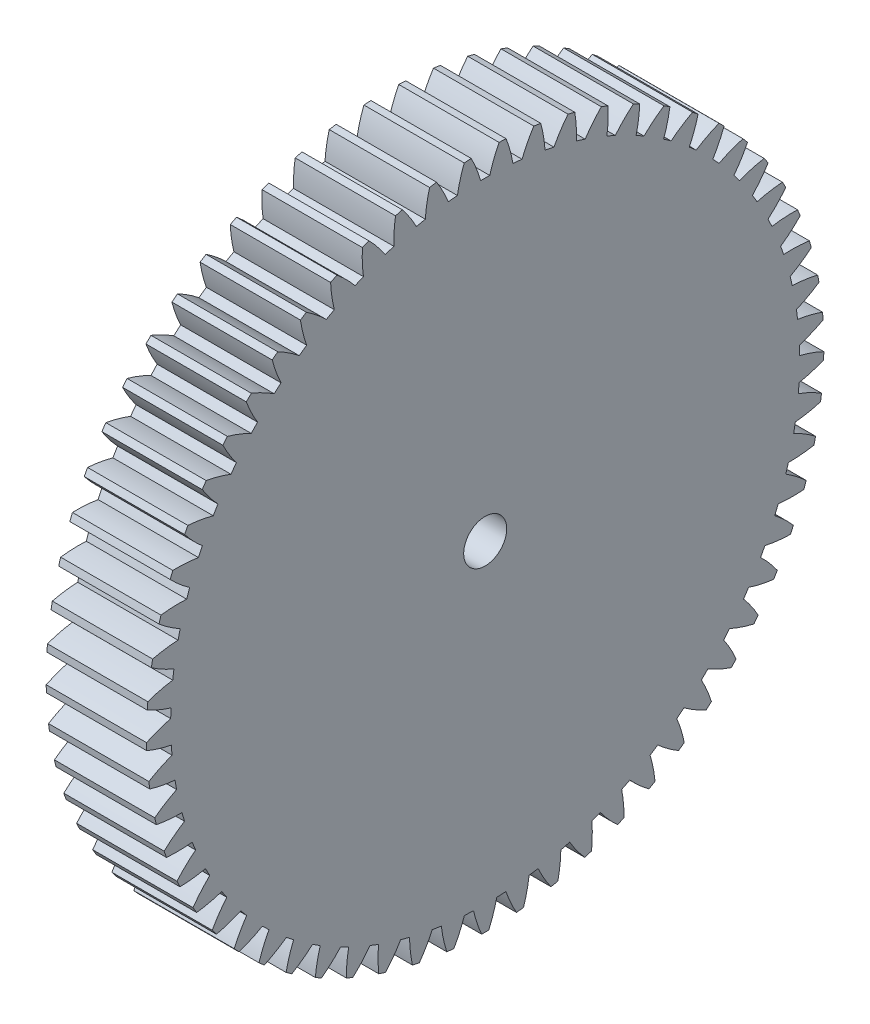
SolidWorks part; units mm, degrees
ref_plane "Plane1" through (0, 0, 0) normal (0, 0, 1) x (1, 0, 0)
ref_plane "Plane2" through (0, 0, 0) normal (0, 1, 0) x (1, 0, 0)
ref_plane "Plane3" through (0, 0, 0) normal (1, 0, 0) x (0, 0, -1)
sketch "HoldingSke" plane through (0, 0, 0) normal (0, 1, 0) x (1, 0, 0)
  line L0 (0, 0) -> (0.3232, -0.5831)
  line L1 (-15, 0) -> (100, 0) construction
  line L2 (0, 0) -> (-2.1039, 2.3779)
  line L3 (0, 0) -> (-11.863, 4.5341)
  line L4 (0, 0) -> (4.1868, 7.5532)
  line L5 (0, 0) -> (-46.8476, -17.4728)
  line L6 (0, 0) -> (-11.6055, -7.8303)
  line L7 (-2.1039, 2.3779) -> (8.6586, 51.2059)
  line L8 (-76.2, 54.61) -> (-75.2, 54.61)
  line L9 (-71.009, 38.7566) -> (-53.1078, 45.2721)
  line L10 (-76.2, 71.12) -> (104.1128, 71.12)
  line L11 (0, 0) -> (-14, 0)
  line L12 (-76.2, 101.6) -> (-76.147, 101.6)
  line L13 (24.9733, 27.94) -> (52.9518, 28.4284)
  line L14 (24.9733, 27.94) -> (24.9743, 27.94)
  line L15 (24.9733, 27.94) -> (100.4006, 29.5858)
  line L16 (-63.627, -1.5) -> (-12.827, -1.5)
  circle A0 centre (0, 0) radius 3
  circle A1 centre (0, 0) radius 37.5
  circle A2 centre (0, 0) radius 37.5
  circle A3 centre (0, 0) radius 3
  dimension "MHD" = 75
  dimension "Hub_dia" = 75
  dimension "Bore" = 6
  dimension "MBD" = 6
  dimension "Num_teeth" = 61
  dimension "Pitch" = 0.6667
  dimension "Overall_len" = 50
  dimension "Show_teeth" = 61
  dimension "Thickness" = 14
  dimension "OAL" = 50.0001
  dimension "T_dim" = 1
  dimension "Ap" = 20
  dimension "H" = 19.05
  dimension "Pitch_radius" = 180.3128
  dimension "Width" = 14
  dimension "Backlash" = 0.053
  dimension "Addendum_fac" = 1
  dimension "Dedendum_fac" = 1.25
  dimension "Clearance_fac" = 0.25
  dimension "Dedendum_add" = 0.001
  dimension "Module" = 1.5
sketch "BasProSke" plane through (0, 0, 0) normal (0, 1, 0) x (1, 0, 0)
  line L0 (-10, 0) -> (60, 0) construction
  line L1 (0, 0) -> (0, 47.25)
  line L2 (0, 0) -> (14, 0)
  line L3 (14, 0) -> (14, 47.25)
  line L4 (14, 47.25) -> (0, 47.25)
  dimension "Thickness" = 14
  dimension "Diameter" = 94.5
revolve "Base-Revolve" add sketch "BasProSke" angle 360 about L0
sketch "TooCutSke" plane through (0, 0, 0) normal (1, 0, 0) x (0, 0, -1)
  line L1 (0, 0) -> (0, 107) construction
  line L2 (0, 0) -> (-1.2707, 45.7323) construction
  line L3 (0, 0) -> (-4.709, 91.353) construction
  line L4 (-1.2707, 45.7323) -> (-2.3545, 45.6765) construction
  arc A0 (0.6377, 43.8694) -> (-0.6377, 43.8694) centre (0, 0) ccw
  arc A1 (1.9534, 47.235) -> (-1.9534, 47.235) centre (0, 0) ccw
  circle A2 centre (0, 0) radius 45.75 construction
  circle A3 centre (0, 0) radius 42.9909 construction
  arc A4 (-0.6377, 43.8694) -> (-1.9534, 47.235) centre (-18.2563, 38.9221) ccw
  arc A5 (1.9534, 47.235) -> (0.6377, 43.8694) centre (18.2563, 38.9221) ccw
  dimension "Root_dia" = 87.748
  dimension "Overcut_dia" = 94.5508
  dimension "Pitch_dia" = 91.5
  dimension "Base_dia" = 85.9819
  dimension "Flank_rad" = 18.3
  dimension "Half_ang" = 2.951
  dimension "Half_CT" = 1.0852
extrude "ToothCut" cut sketch "TooCutSke" along normal through all
fillet "Breaks" [suppressed] radius 0.03
fillet "RootFillets" [suppressed] radius 0.376
pattern_circular "TeethCuts" count 61 every 5.902 about axis through (-10, 0, 0) along (1, 0, 0) of "ToothCut", "RootFillets", "Breaks"
sketch "HubNeaOneSke" plane through (0, 0, 0) normal (-1, 0, 0) x (0, 0, 1)
  circle A0 centre (0, 0) radius 37.5
  dimension "Diameter" = 75
extrude "HubNearOne" [suppressed] add sketch "HubNeaOneSke" along normal blind 36.0001
sketch "HubNeaBotSke" plane through (0, 0, 0) normal (-1, 0, 0) x (0, 0, 1)
  circle A0 centre (0, 0) radius 37.5
  dimension "Diameter" = 75
extrude "HubNearBoth" [suppressed] add sketch "HubNeaBotSke" along normal blind 18
ref_plane "FarPln" through (14, 0, 0) normal (1, 0, 0) x (0, 0, -1)
sketch "HubFarSke" plane through (14, 0, 0) normal (1, 0, 0) x (0, 0, -1)
  circle A0 centre (0, 0) radius 37.5
  dimension "Diameter" = 75
extrude "HubFar" [suppressed] add sketch "HubFarSke" along normal blind 18
sketch "BorSke" plane through (0, 0, 0) normal (1, 0, 0) x (0, 0, -1)
  circle A0 centre (0, 0) radius 3
  dimension "Diameter" = 6
extrude "Bore" cut sketch "BorSke" along normal mid plane 100.0001
sketch "KeySke" plane through (0, 0, 0) normal (1, 0, 0) x (0, 0, -1)
  line L0 (-1, 0) -> (-1, 4)
  line L1 (-1, 4) -> (1, 4)
  line L2 (1, 4) -> (1, 0)
  line L3 (0, 0) -> (0, 34) construction
  line L4 (-1, 0) -> (1, 0)
  dimension "Offset" = 4
  dimension "Width" = 2
extrude "Keyway" [suppressed] cut sketch "KeySke" along normal mid plane 100.0001
pattern_circular "Keyway2" [suppressed] count 2 every 90 about axis through (-10, 0, 0) along (1, 0, 0)
equation "' \"Module@HoldingSke\" = 6.35"
equation "' \"Num_teeth@HoldingSke\" = 12"
equation "' \"Ap@HoldingSke\" =  20"
equation "' \"Ap@HoldingSke\" = 20"
equation "' \"Width@HoldingSke\" = 0.5 * 25.4"
equation "' \"Hub_dia@HoldingSke\"= 1 * 25.4"
equation "' \"Hub_dia@HoldingSke\" = 1 * 25.4"
equation "' \"Overall_len@HoldingSke\" = 1.0 * 25.4"
equation "' \"Bore@HoldingSke\" = 0.75 * 25.4"
equation "' \"T_dim@HoldingSke\" = 0.1 * 25.4"
equation "' \"Width@KeySke\" = 0.25 * 25.4"
equation "' \"Show_teeth@HoldingSke\" = 13"
equation "' \"Backlash@HoldingSke\" = 0.009 * 25.4"
equation "' \"Addendum_fac@HoldingSke\" = 1.0"
equation "' \"Dedendum_fac@HoldingSke\" = 1.25"
equation "' \"Dedendum_add@HoldingSke\" = 0.00005 * 25.4"
equation "' \"Clearance_fac@HoldingSke\" = 0.25"
equation "\"Pitch@HoldingSke\" = 1 / \"Module@HoldingSke\""
equation "\"Overcut_dia@TooCutSke\" = (\"Num_teeth@HoldingSke\" + 2 * \"Addendum_fac@HoldingSke\") / \"Pitch@HoldingSke\" + 0.002 * 25.4"
equation "\"Pitch_dia@TooCutSke\" = \"Num_teeth@HoldingSke\" / \"Pitch@HoldingSke\""
equation "\"Base_dia@TooCutSke\" = \"Num_teeth@HoldingSke\" / \"Pitch@HoldingSke\" * cos((\"Ap@HoldingSke\"  * 3.14159265 / 180))"
equation "\"Root_dia@TooCutSke\" = (\"Num_teeth@HoldingSke\" + 2) / \"Pitch@HoldingSke\" - 2 * (\"Addendum_fac@HoldingSke\" + \"Dedendum_fac@HoldingSke\") / \"Pitch@HoldingSke\" - \"Dedendum_add@HoldingSke\" * 2"
equation "\"Half_ang@TooCutSke\" = 180 / \"Num_teeth@HoldingSke\""
equation "\"Half_CT@TooCutSke\" = \"Num_teeth@HoldingSke\" / \"Pitch@HoldingSke\" * sin((3.14159265 / 2 / \"Num_teeth@HoldingSke\")) / 2 - 7 * \"Backlash@HoldingSke\" / 4"
equation "\"Flank_rad@TooCutSke\" = \"Num_teeth@HoldingSke\" / \"Pitch@HoldingSke\" / 5"
equation "\"Radius@RootFillets\" = \"Clearance_fac@HoldingSke\" / \"Pitch@HoldingSke\" + \"Dedendum_add@HoldingSke\""
equation "\"Break_rad@Breaks\" = 0.02 / \"Pitch@HoldingSke\""
equation "\"Thickness@HoldingSke\" = \"Width@HoldingSke\""
equation "\"OAL@HoldingSke\" = \"Thickness@HoldingSke\""
equation "\"MHD@HoldingSke\" = (\"Num_teeth@HoldingSke\" + 2) / \"Pitch@HoldingSke\" - 2 * (\"Addendum_fac@HoldingSke\" + \"Dedendum_fac@HoldingSke\")  / \"Pitch@HoldingSke\" - \"Dedendum_add@HoldingSke\" * 2"
equation "\"MBD@HoldingSke\" = (\"Num_teeth@HoldingSke\" + 2) / \"Pitch@HoldingSke\" - 2 * (\"Addendum_fac@HoldingSke\" + \"Dedendum_fac@HoldingSke\")  / \"Pitch@HoldingSke\" - \"Dedendum_add@HoldingSke\" * 2 - 0.002 * 25.4"
equation "\"MHD@HoldingSke\" = ((sgn( \"MHD@HoldingSke\" - \"Hub_dia@HoldingSke\" )-1)*( \"MHD@HoldingSke\" - \"Hub_dia@HoldingSke\" ))/-2+ \"Hub_dia@HoldingSke\""
equation "\"MBD@HoldingSke\" = ((sgn( \"MBD@HoldingSke\" - \"Bore@HoldingSke\" )-1)*( \"MBD@HoldingSke\" - \"Bore@HoldingSke\" ))/-2+ \"Bore@HoldingSke\""
equation "\"OAL@HoldingSke\" = ((sgn( \"OAL@HoldingSke\" - \"Overall_len@HoldingSke\" )+1)*( \"OAL@HoldingSke\" - \"Overall_len@HoldingSke\" ))/2 + \"Overall_len@HoldingSke\" + 0.000002 * 25.4"
equation "\"Num_teeth@TeethCuts\" = int( \"Show_teeth@HoldingSke\" ) + 1"
equation "\"Num_teeth@TeethCuts\" = ((sgn( \"Num_teeth@TeethCuts\" - \"Num_teeth@HoldingSke\" )-1)*( \"Num_teeth@TeethCuts\" - \"Num_teeth@HoldingSke\" ))/-2+ \"Num_teeth@HoldingSke\""
equation "\"Num_teeth@TeethCuts\" = ((sgn( \"Num_teeth@TeethCuts\" - 2.0)+1)*( \"Num_teeth@TeethCuts\" - 2.0))/2 +2.0"
equation "\"Angle@TeethCuts\" = 360.0 / \"Num_teeth@HoldingSke\""
equation "\"Diameter@BasProSke\" = (\"Num_teeth@HoldingSke\" + 2 * \"Addendum_fac@HoldingSke\") / \"Pitch@HoldingSke\""
equation "\"Thickness@BasProSke\"  = \"Thickness@HoldingSke\""
equation "' \"Fillet_rad@BasProSke\" =  \"Thickness@HoldingSke\" * 0.05"
equation "' \"Fillet_rad@BasProSke\" = \"Thickness@HoldingSke\" * 0.05"
equation "\"MHD@HoldingSke\" = ((sgn( \"MHD@HoldingSke\" - \"Root_dia@TooCutSke\" )-1)*( \"MHD@HoldingSke\" - \"Root_dia@TooCutSke\" ))/-2+ \"Root_dia@TooCutSke\""
equation "\"Diameter@HubNeaOneSke\" = \"MHD@HoldingSke\""
equation "\"Length@HubNearOne\" = \"OAL@HoldingSke\" - \"Thickness@BasProSke\""
equation "\"Diameter@HubNeaBotSke\" = \"MHD@HoldingSke\""
equation "\"Length@HubNearBoth\" = ( \"OAL@HoldingSke\" - \"Thickness@BasProSke\" ) / 2.0"
equation "\"Thickness@FarPln\" = \"Thickness@BasProSke\""
equation "\"Diameter@HubFarSke\" = \"MHD@HoldingSke\""
equation "\"Length@HubFar\" = ( \"OAL@HoldingSke\" - \"Thickness@BasProSke\" ) / 2.0"
equation "\"Diameter@BorSke\" = \"MBD@HoldingSke\""
equation "\"D1@Bore\" = \"OAL@HoldingSke\" * 2.0"
equation "\"D1@Keyway\" = \"OAL@HoldingSke\" * 2.0"
equation "\"Offset@KeySke\" = \"T_dim@HoldingSke\" + \"MBD@HoldingSke\" / 2.0"
